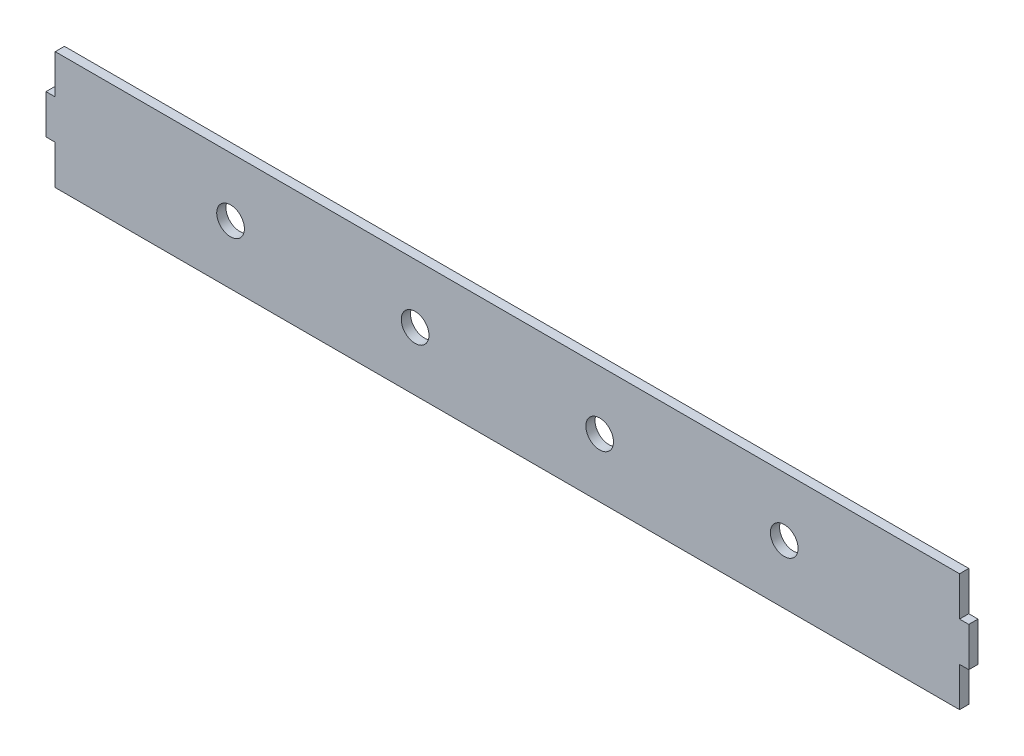
SolidWorks part; units mm, degrees
material "Contreplaqué pin"
ref_plane "Plan de face" through (0, 0, 0) normal (0, 0, 1) x (1, 0, 0)
ref_plane "Plan de dessus" through (0, 0, 0) normal (0, 1, 0) x (1, 0, 0)
ref_plane "Plan de droite" through (0, 0, 0) normal (1, 0, 0) x (0, 0, -1)
sketch "Esquisse1" plane through (0, 0, 0) normal (0, 0, 1) x (1, 0, 0)
  line L0 (0, 0) -> (0, 21.2667)
  line L1 (0, 21.2667) -> (-5, 21.2667)
  line L2 (-5, 21.2667) -> (-5, 42.5333)
  line L3 (-5, 42.5333) -> (0, 42.5333)
  line L4 (0, 42.5333) -> (0, 63.8)
  line L5 (0, 63.8) -> (490, 63.8)
  line L6 (490, 63.8) -> (490, 42.5333)
  line L7 (490, 42.5333) -> (495, 42.5333)
  line L8 (495, 42.5333) -> (495, 21.2667)
  line L9 (495, 21.2667) -> (490, 21.2667)
  line L10 (490, 21.2667) -> (490, 0)
  line L11 (490, 0) -> (0, 0)
  line L12 (-5, 31.9) -> (95, 31.9) construction
  line L13 (95, 31.9) -> (195, 31.9) construction
  line L14 (195, 31.9) -> (295, 31.9) construction
  line L15 (295, 31.9) -> (395, 31.9) construction
  line L16 (395, 31.9) -> (495, 31.9) construction
  circle A0 centre (95, 31.9) radius 7.5
  circle A1 centre (195, 31.9) radius 7.5
  circle A2 centre (295, 31.9) radius 7.5
  circle A3 centre (395, 31.9) radius 7.5
  dimension "D5" = 15
  dimension "D1" = 500
  dimension "D2" = 63.8
  dimension "D3" = 5
  dimension "D4" = 5
extrude "Boss.-Extru.1" add sketch "Esquisse1" along normal blind 5
